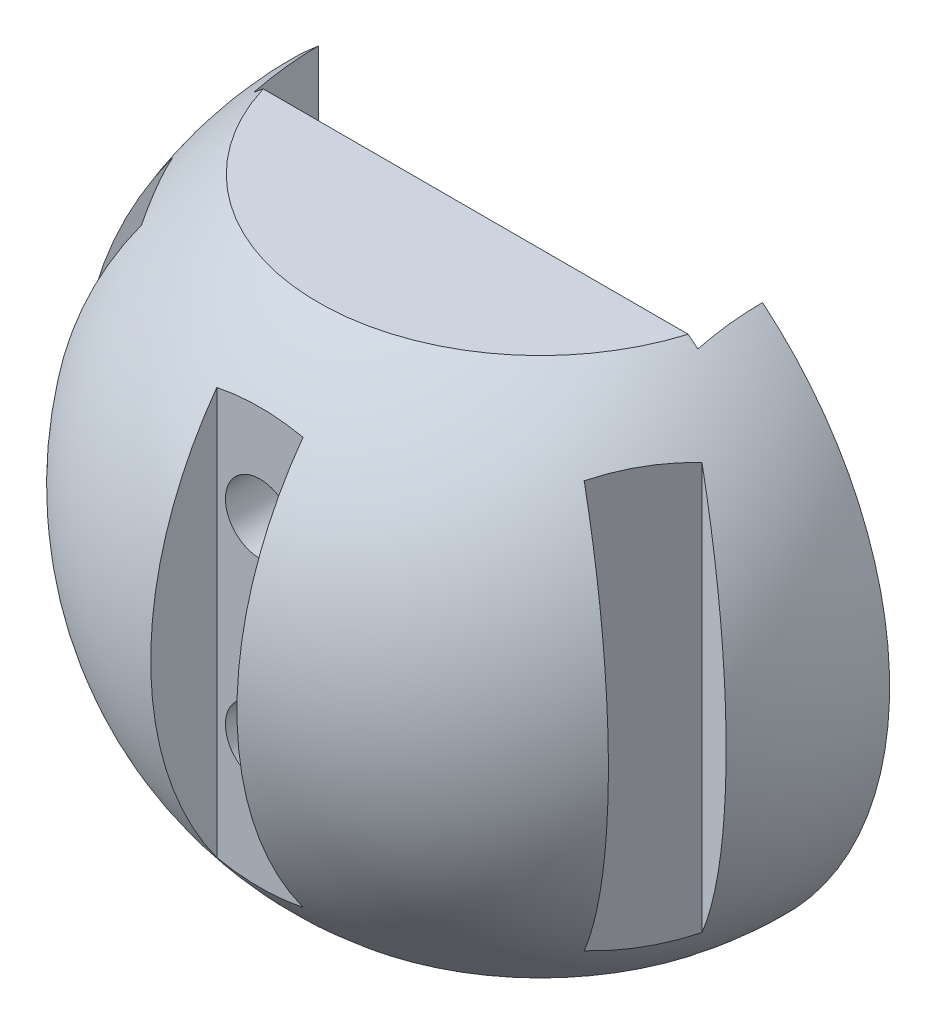
SolidWorks part; units mm, degrees
material "petg 20%"
ref_plane "Front Plane" through (0, 0, 0) normal (0, 0, 1) x (1, 0, 0)
ref_plane "Top Plane" through (0, 0, 0) normal (0, 1, 0) x (1, 0, 0)
ref_plane "Right Plane" through (0, 0, 0) normal (1, 0, 0) x (0, 0, -1)
sketch "Sketch1" plane through (0, 0, 0) normal (0, 0, 1) x (1, 0, 0)
  line L1 (0, 24.3) -> (0, -8.1)
  arc A1 (0, 24.3) -> (0, -8.1) centre (0, 8.1) cw
  dimension "D1" = 16.2
revolve "Revolve6" add sketch "Sketch1" angle 180 about L1
sketch "Sketch6" plane through (0, 0, 0) normal (0, 0, -1) x (-1, 0, 0)
  line L1 (10.3033, 20.6013) -> (-10.3033, 20.6013)
  line L2 (10.3033, 20.6013) -> (10.3033, -4.4013)
  line L3 (10.3033, -4.4013) -> (-10.3033, -4.4013)
  line L4 (-10.3033, 20.6013) -> (-10.3033, -4.4013)
  line L5 (10.3033, 20.6013) -> (-10.3033, -4.4013) construction
  line L6 (10.3033, -4.4013) -> (-10.3033, 20.6013) construction
  circle A0 centre (0, 8.1) radius 16.2 construction
  point P0 (0, 8.1)
  point P1 (0, 8.1)
sketch "Sketch7" plane through (0, 0, 0) normal (0, 0, -1) x (-1, 0, 0)
  line L0 (-10.3033, 20.6013) -> (10.3033, 20.6013)
  line L1 (-10.3033, -4.4013) -> (10.3033, -4.4013)
  arc A0 (-10.3033, 20.6013) -> (10.3033, 20.6013) centre (0, 8.1) cw
  arc A1 (-10.3033, -4.4013) -> (10.3033, -4.4013) centre (0, 8.1) ccw
extrude "Cut-Extrude3" cut sketch "Sketch7" against normal through all
extrude "Cut-Extrude4" cut sketch "Sketch6" against normal blind 3
sketch "Sketch15" plane through (0, 0, 0) normal (1, 0, 0) x (0, 0, -1)
  line L0 (-13.0115, 20.6013) -> (-13.0115, -5.8514)
  line L1 (-13.0115, 20.6013) -> (-18.1365, 20.6013)
  line L2 (-13.0115, -5.8514) -> (-18.1365, -5.8514)
  line L3 (-18.1365, 20.6013) -> (-18.1365, -5.8514)
extrude "Cut-Extrude7" cut sketch "Sketch15" against normal mid plane 4
pattern_circular "CirPattern1" count 6 over 360 about axis through (0, 0, 0) along (0, 1, 0) of "Cut-Extrude7"
sketch "Sketch20" plane through (0, 0, 13.0115) normal (0, 0, 1) x (1, 0, 0)
  line L0 (0, -0.6939) -> (0, 25.6879) construction
  circle A0 centre (0, 13.2676) radius 1.6
  circle A1 centre (0, 4.2154) radius 1.6
  dimension "D1" = 3.2
  dimension "D2" = 3.2
extrude "Cut-Extrude8" cut sketch "Sketch20" against normal through all
